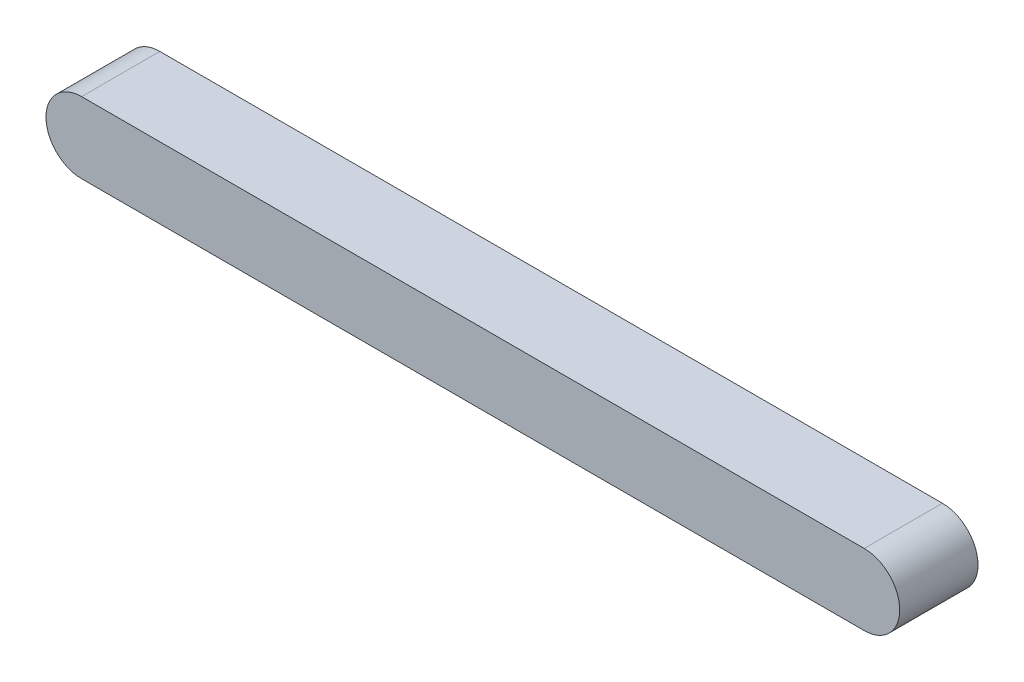
SolidWorks part; units mm, degrees
ref_plane "Front Plane" through (0, 0, 0) normal (0, 0, 1) x (1, 0, 0)
ref_plane "Top Plane" through (0, 0, 0) normal (0, 1, 0) x (1, 0, 0)
ref_plane "Right Plane" through (0, 0, 0) normal (1, 0, 0) x (0, 0, -1)
sketch "Sketch1" plane through (0, 0, 0) normal (0, 0, 1) x (1, 0, 0)
  line L0 (-11, 0) -> (11, 0) construction
  line L1 (-11, 1) -> (11, 1)
  line L2 (-11, -1) -> (11, -1)
  arc A0 (-11, 1) -> (-11, -1) centre (-11, 0) ccw
  arc A1 (11, -1) -> (11, 1) centre (11, 0) ccw
  point P3 (0, 0)
  dimension "D2" = 1
  dimension "D1" = 22
  dimension "D3" = 11
extrude "Boss-Extrude1" add sketch "Sketch1" along normal blind 2.2
